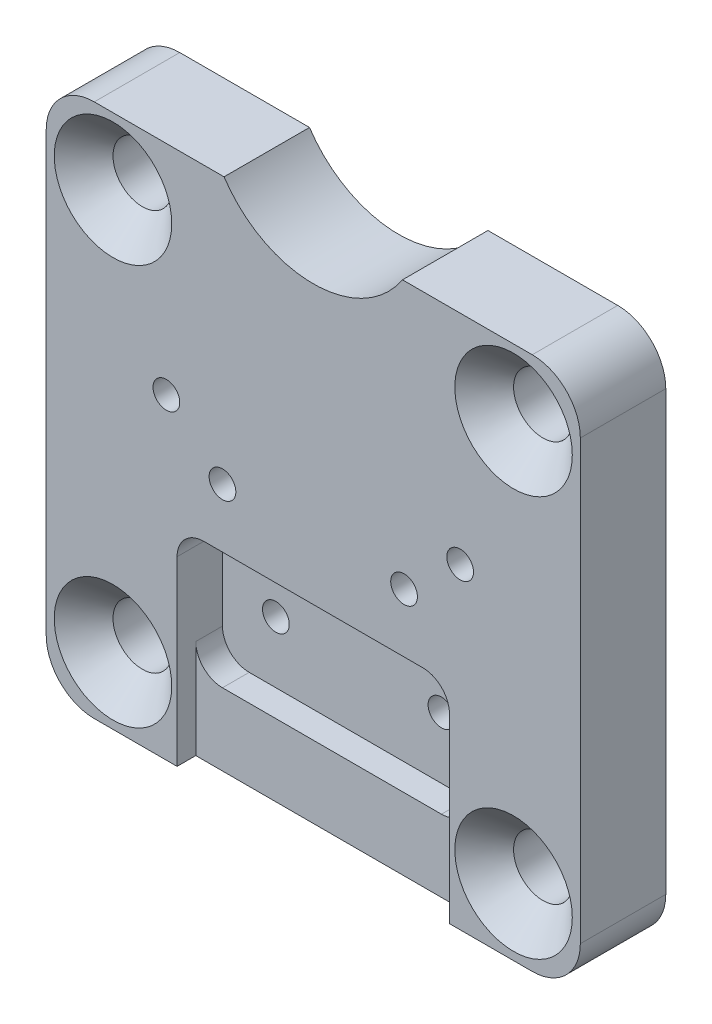
SolidWorks part; units mm, degrees
ref_plane "Plan de face" through (0, 0, 0) normal (0, 0, 1) x (1, 0, 0)
ref_plane "Plan de dessus" through (0, 0, 0) normal (0, 1, 0) x (1, 0, 0)
ref_plane "Plan de droite" through (0, 0, 0) normal (1, 0, 0) x (0, 0, -1)
sketch "Esquisse1" plane through (0, 0, 0) normal (0, 0, 1) x (1, 0, 0)
  line L1 (10, -10) -> (-10, -10)
  line L2 (10, -10) -> (10, 10)
  line L3 (10, 10) -> (-10, 10)
  line L4 (-10, -10) -> (-10, 10)
  line L5 (10, -10) -> (-10, 10) construction
  line L6 (10, 10) -> (-10, -10) construction
  point P0 (0, 0)
  dimension "D1" = 20
extrude "Boss.-Extru.1" add sketch "Esquisse1" along normal blind 3.2
fillet "Congé1" radius 1.8 4 edges at (-10, -10, 1.6) (10, -10, 1.6) (-10, 10, 1.6) (10, 10, 1.6)
hole_wizard "Diamètre du perçage Ø1.0 (1)1" positions "Esquisse3" profile "Esquisse2" hole size "Ø1.0" standard "ISO" end condition through all
sketch "Esquisse3" plane through (0, 0, 3.2) normal (0, 0, 1) x (1, 0, 0)
  line L0 (-3.4, 0) -> (3.4, 0) construction
  line L3 (0, 0) -> (0, -5) construction
  line L6 (-3.1, -5) -> (3.1, -5) construction
  line L9 (0, 0) -> (0, 1.85) construction
  line L12 (-5.5, 1.85) -> (5.5, 1.85) construction
  point P30 (3.1, -5)
  point P32 (3.4, 0)
  point P34 (5.5, 1.85)
  point P36 (-5.5, 1.85)
  point P38 (-3.4, 0)
  point P40 (-3.1, -5)
  dimension "D1" = 6.8
  dimension "D2" = 11
  dimension "D3" = 6.2
  dimension "D4" = 5
  dimension "D5" = 1.85
sketch "Esquisse2" plane through (3.1, -5, 3.2) normal (1, 0, 0) x (0, -1, 0)
  line L0 (0, 0) -> (0, 3.2)
  line L1 (0, 3.2) -> (0.5, 3.2)
  line L2 (0.5, 3.2) -> (0.5, 0)
  line L5 (0.5, 0) -> (0, 0)
  line L11 (0, -6.35) -> (0, 107.95) construction
  dimension "Diamètre du perçage jusqu'au prochain" = 1
  dimension "Profondeur du perçage jusqu'au prochain" = 3.2
sketch "Esquisse4" plane through (0, 0, 3.2) normal (0, 0, 1) x (1, 0, 0)
  line L0 (-8.2, -10) -> (8.2, -10) construction
  line L1 (-5.1, -10) -> (5.1, -10)
  line L2 (-5.1, -10) -> (-5.1, -2.2)
  line L3 (-5.1, -2.2) -> (5.1, -2.2)
  line L4 (5.1, -10) -> (5.1, -2.2)
  line L5 (0, 0) -> (0, -2.2) construction
  dimension "D1" = 10.2
  dimension "D2" = 2.2
extrude "Enlèv. mat.-Extru.1" cut sketch "Esquisse4" against normal blind 0.7
sketch "Esquisse5" plane through (0, 0, 2.5) normal (0, 0, 1) x (1, 0, 0)
  line L0 (5.1, -10) -> (5.1, -2.2) construction
  line L1 (-5.1, -2.2) -> (5.1, -2.2)
  line L2 (-5.1, -2.2) -> (-5.1, -7.3)
  line L3 (-5.1, -7.3) -> (5.1, -7.3)
  line L4 (5.1, -2.2) -> (5.1, -7.3)
  dimension "D1" = 7.3
extrude "Enlèv. mat.-Extru.2" cut sketch "Esquisse5" against normal blind 1
fillet "Congé2" radius 1 4 edges at (5.1, -7.3, 2) (-5.1, -7.3, 2) (5.1, -2.2, 2.35) (-5.1, -2.2, 2.35)
hole_wizard "Fraisage pour vis à tête fraisée M21" positions "Esquisse7" profile "Esquisse6" countersink size "M2" standard "ISO" end condition through all
sketch "Esquisse7" plane through (0, 0, 3.2) normal (0, 0, 1) x (1, 0, 0)
  line L1 (7.5, -7.5) -> (-7.5, -7.5)
  line L2 (7.5, -7.5) -> (7.5, 7.5)
  line L3 (7.5, 7.5) -> (-7.5, 7.5)
  line L4 (-7.5, -7.5) -> (-7.5, 7.5)
  line L5 (7.5, -7.5) -> (-7.5, 7.5) construction
  line L6 (7.5, 7.5) -> (-7.5, -7.5) construction
  point P0 (-7.5, 7.5)
  point P78 (-7.5, -7.5)
  point P80 (7.5, -7.5)
  point P82 (7.5, 7.5)
  dimension "D1" = 15
sketch "Esquisse6" plane through (-7.5, 7.5, 3.2) normal (1, 0, 0) x (0, -1, 0)
  line L0 (0, 0) -> (0, 3.2)
  line L1 (0, 3.2) -> (1.1, 3.2)
  line L2 (1.1, 3.2) -> (1.1, 1.1)
  line L3 (1.1, 1.1) -> (2.2, 0)
  line L5 (2.2, 0) -> (0, 0)
  line L6 (-1.1, 1.1) -> (-2.2, 0) construction
  line L11 (0, -6.35) -> (0, 107.95) construction
  dimension "Diamètre du perçage jusqu'au prochain" = 2.2
  dimension "Profondeur du perçage jusqu'au prochain" = 3.2
  dimension "Diamètre du fraisage entrant" = 4.4
  dimension "Angle du fraisage entrant" = 90
sketch "Esquisse8" plane through (0, 0, 3.2) normal (0, 0, 1) x (1, 0, 0)
  line L0 (0, 0) -> (0, 12.2) construction
  circle A0 centre (0, 12.2) radius 4
  dimension "D2" = 8
  dimension "D1" = 12.2
extrude "Enlèv. mat.-Extru.3" cut sketch "Esquisse8" against normal through all
